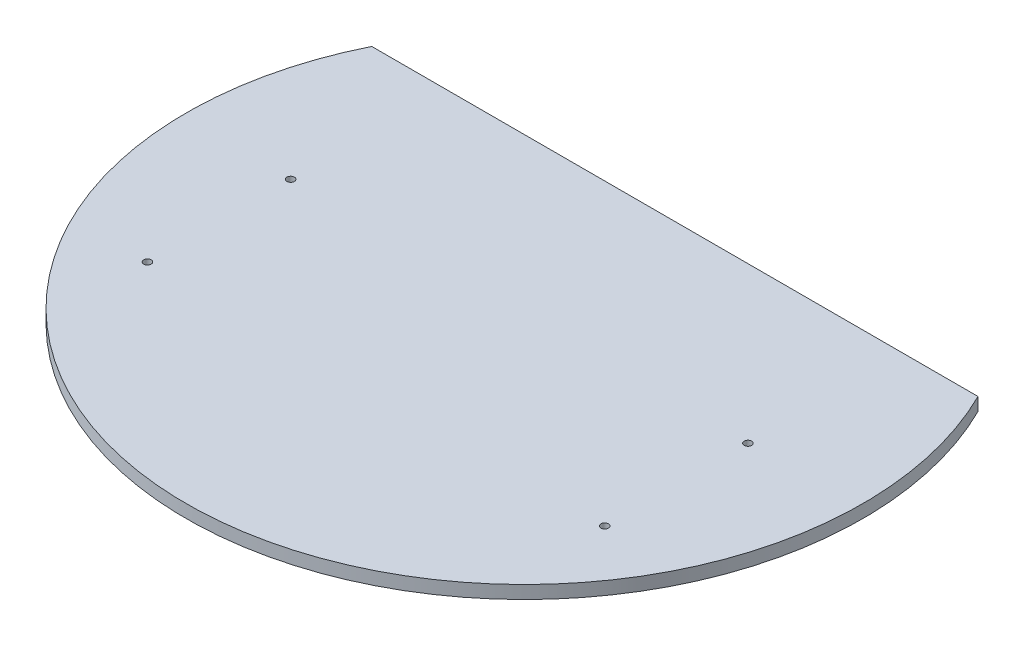
SolidWorks part; units mm, degrees
material "ABS"
ref_plane "Front Plane" through (0, 0, 0) normal (0, 0, 1) x (1, 0, 0)
ref_plane "Top Plane" through (0, 0, 0) normal (0, 1, 0) x (1, 0, 0)
ref_plane "Right Plane" through (0, 0, 0) normal (1, 0, 0) x (0, 0, -1)
sketch "Sketch1" plane through (0, 0, 0) normal (0, 1, 0) x (1, 0, 0)
  circle A0 centre (0, 0) radius 164.975
  dimension "D1" = 329.95
extrude "Boss-Extrude1" add sketch "Sketch1" along normal blind 6.35
ref_point "Point1"
hole_wizard "#6 Clearance Hole1" positions "3DSketch1" profile "Sketch2" hole size "#6" standard "Ansi Inch" end condition through all
sketch3d "3DSketch1"
  line L0 (0, 0, 0) -> (213.1626, 0, 0) construction
  line L2 (0, 0, 0) -> (0, 0, 209.6006) construction
  point P20 (111.465, 0, 2.54)
  point P22 (111.465, 0, 72.39)
  point P26 (111.465, 0, 2.54)
  point P28 (-111.465, 0, 72.39)
  point P29 (-111.465, 0, 2.54)
  dimension "D1" = 2.54
  dimension "D2" = 111.465
  dimension "D3" = 111.465
  dimension "D4" = 69.85
  dimension "D5" = 111.465
  dimension "D6" = 2.54
  dimension "D7" = 69.85
  dimension "D8" = 111.465
sketch "Sketch2" plane through (111.465, 0, 2.54) normal (1, 0, 0) x (0, 0, -1)
  line L0 (0, 0) -> (0, 6.35)
  line L1 (0, 6.35) -> (1.8288, 6.35)
  line L2 (1.8288, 6.35) -> (1.8288, 0)
  line L5 (1.8288, 0) -> (0, 0)
  line L11 (0, -6.35) -> (0, 107.95) construction
  dimension "Thru Hole Dia." = 3.6576
  dimension "Thru Hole Depth" = 6.35
sketch "Sketch9" plane through (0, 6.35, 0) normal (0, 1, 0) x (1, 0, 0)
  line L0 (-44.45, -69.974) -> (44.45, -158.874) construction
  line L1 (-44.45, -158.874) -> (44.45, -69.974) construction
  line L2 (44.45, -158.874) -> (44.45, -69.974) construction
  line L3 (44.45, -69.974) -> (-44.45, -69.974) construction
  line L4 (0, -114.424) -> (0, 73.3074) construction
  line L5 (-147.793, 73.3074) -> (147.793, 73.3074)
  circle A0 centre (0, 0) radius 164.975 construction
  arc A1 (-147.793, 73.3074) -> (147.793, 73.3074) centre (0, 0) cw
extrude "Cut-Extrude1" cut sketch "Sketch9" against normal blind 6.35
